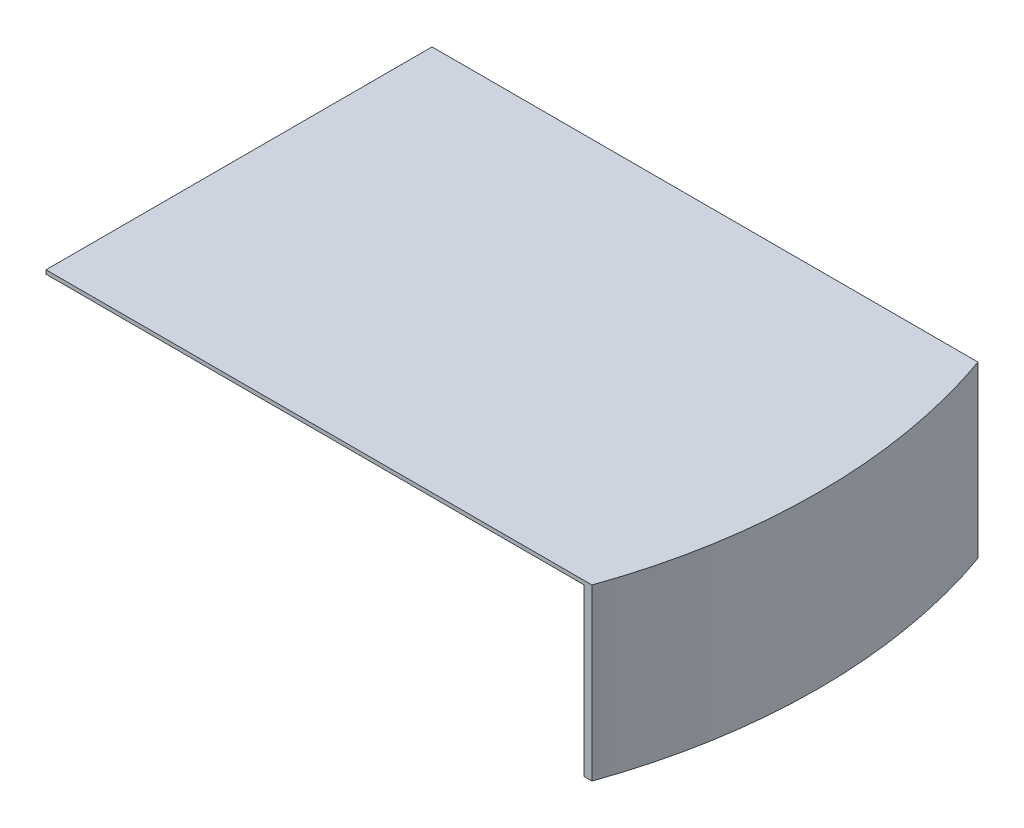
SolidWorks part; units mm, degrees
ref_plane "Front Plane" through (0, 0, 0) normal (0, 0, 1) x (1, 0, 0)
ref_plane "Top Plane" through (0, 0, 0) normal (0, 1, 0) x (1, 0, 0)
ref_plane "Right Plane" through (0, 0, 0) normal (1, 0, 0) x (0, 0, -1)
sketch "Sketch1" plane through (0, 0, 0) normal (0, 1, 0) x (1, 0, 0)
  line L0 (0, 0) -> (0, 50)
  line L1 (0, 0) -> (0, -50)
  line L2 (0, 50) -> (141.4214, 50)
  line L3 (0, -50) -> (141.4214, -50)
  arc A0 (141.4214, -50) -> (141.4214, 50) centre (0, 0) ccw
  point P3 (0, 75)
  point P6 (0, -75)
  point P7 (0, 50)
  point P8 (0, -50)
  dimension "D1" = 300
extrude "Boss-Extrude1" add sketch "Sketch1" along normal blind 44
shell "Shell1" thickness 2
sketch "Sketch3" plane through (0, 42, 0) normal (0, -1, 0) x (1, 0, 0)
  line L0 (0, 30) -> (144.9276, 30)
  line L1 (0, -50) -> (0, 50) construction
  line L2 (0, 30) -> (0, 50)
  line L3 (0, 50) -> (139.2982, 50)
  arc A0 (139.2982, -50) -> (139.2982, 50) centre (0, 0) ccw construction
  arc A1 (144.9276, 30) -> (139.2982, 50) centre (0, 0) ccw
  dimension "D1" = 20
extrude "Cut-Extrude1" cut sketch "Sketch3" against normal blind 1
